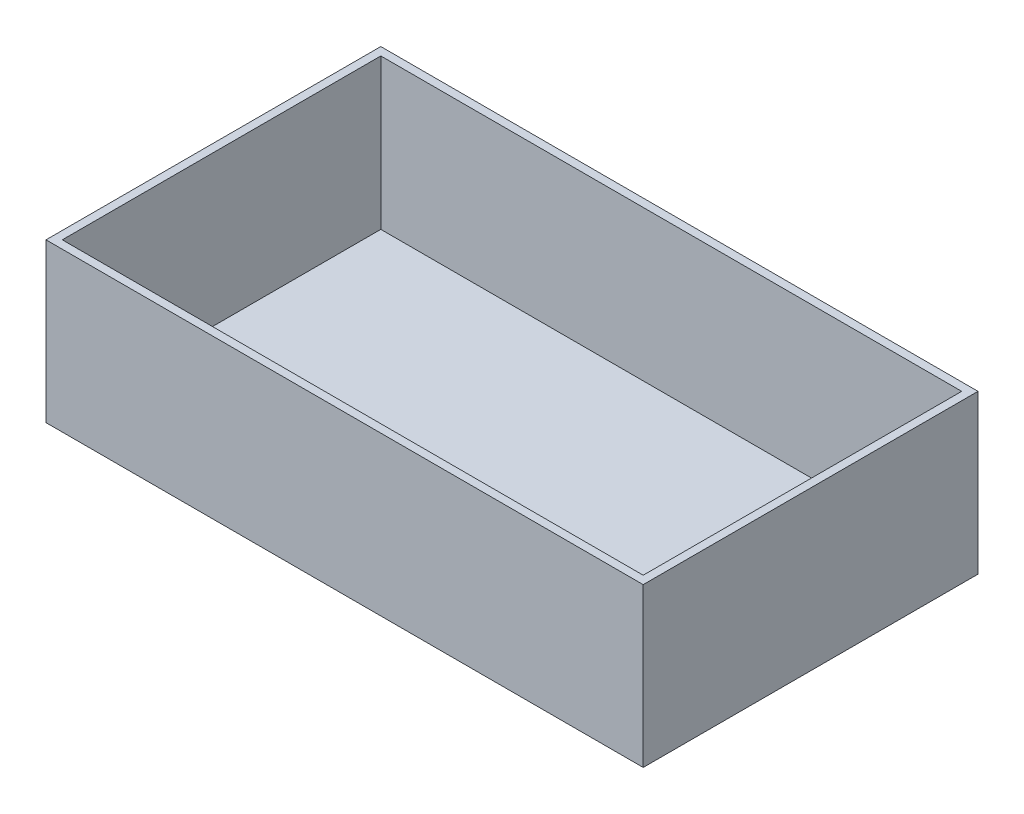
SolidWorks part; units mm, degrees
material "Haya"
ref_plane "Alzado" through (0, 0, 0) normal (0, 0, 1) x (1, 0, 0)
ref_plane "Planta" through (0, 0, 0) normal (0, 1, 0) x (1, 0, 0)
ref_plane "Vista lateral" through (0, 0, 0) normal (1, 0, 0) x (0, 0, -1)
sketch "Croquis1" plane through (0, 0, 0) normal (0, 1, 0) x (1, 0, 0)
  line L1 (-660, -370) -> (660, -370)
  line L2 (-660, -370) -> (-660, 370)
  line L3 (-660, 370) -> (660, 370)
  line L4 (660, -370) -> (660, 370)
  line L5 (-660, -370) -> (660, 370) construction
  line L6 (-660, 370) -> (660, -370) construction
  point P0 (0, 0)
  dimension "D1" = 740
  dimension "D2" = 1320
extrude "Saliente-Extruir1" add sketch "Croquis1" along normal blind 350
sketch "Croquis2" plane through (0, 350, 0) normal (0, 1, 0) x (1, 0, 0)
  line L1 (-642, -352) -> (642, -352)
  line L2 (-642, -352) -> (-642, 352)
  line L3 (-642, 352) -> (642, 352)
  line L4 (642, -352) -> (642, 352)
  line L5 (-642, -352) -> (642, 352) construction
  line L6 (-642, 352) -> (642, -352) construction
  point P0 (0, 0)
  dimension "D1" = 704
  dimension "D2" = 1284
extrude "Cortar-Extruir1" cut sketch "Croquis2" against normal blind 332
